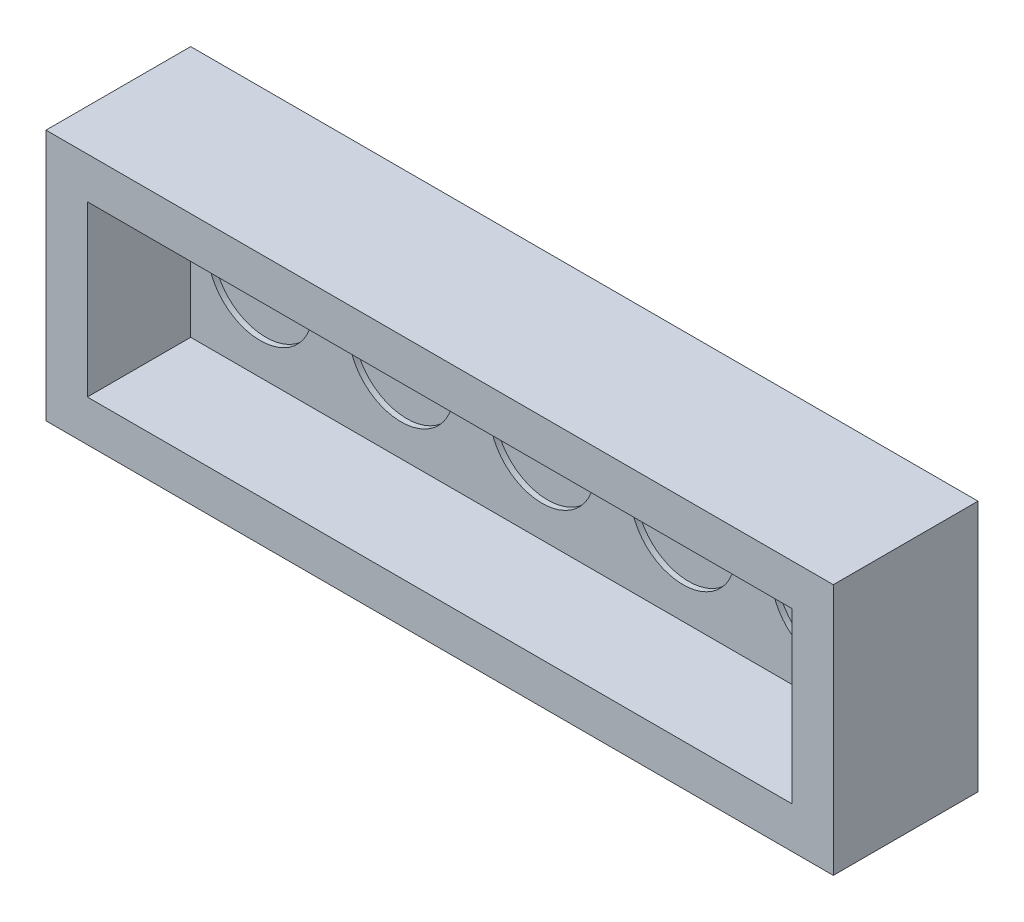
SolidWorks part; units mm, degrees
ref_plane "Front Plane" through (0, 0, 0) normal (0, 0, 1) x (1, 0, 0)
ref_plane "Top Plane" through (0, 0, 0) normal (0, 1, 0) x (1, 0, 0)
ref_plane "Right Plane" through (0, 0, 0) normal (1, 0, 0) x (0, 0, -1)
sketch "Esquisse1" plane through (0, 0, 0) normal (0, 0, 1) x (1, 0, 0)
  line L1 (0, 0) -> (419, 0)
  line L2 (0, 0) -> (0, -134)
  line L3 (0, -134) -> (419, -134)
  line L4 (419, 0) -> (419, -134)
  dimension "D1" = 419
  dimension "D2" = 134
extrude "Boss.-Extru.1" add sketch "Esquisse1" along normal blind 22
sketch "Esquisse3" plane through (0, 0, 22) normal (0, 0, 1) x (1, 0, 0)
  line L0 (0, -134) -> (0, 0)
  line L1 (0, 0) -> (0, -134) construction
  line L2 (0, 0) -> (419, 0)
  line L3 (419, -134) -> (419, 0) construction
  line L4 (419, 0) -> (419, -134)
  line L7 (397, -112) -> (397, -22)
  line L8 (397, -22) -> (22, -22)
  line L9 (22, -22) -> (22, -112)
  line L10 (419, 0) -> (0, 0) construction
  line L12 (22, -112) -> (397, -112)
  line L13 (0, -134) -> (419, -134)
  point P12 (22, -93.7254)
  dimension "D1" = 22
  dimension "D2" = 22
  dimension "D3" = 22
  dimension "D4" = 22
extrude "Boss.-Extru.2" add sketch "Esquisse3" along normal blind 55
sketch "Esquisse4" plane through (0, 0, 22) normal (0, 0, 1) x (1, 0, 0)
  line L1 (22, -112) -> (22, -22) construction
  line L2 (22, -112) -> (397, -112) construction
  circle A0 centre (59, -67) radius 28
  circle A1 centre (134, -67) radius 28
  circle A2 centre (209, -67) radius 28
  circle A3 centre (284, -67) radius 28
  circle A4 centre (359, -67) radius 28
  point P3 (60.754, -67.138)
  point P11 (0, 0)
  dimension "D1" = 56
  dimension "D3" = 45
  dimension "D4" = 37
  dimension "D2" = 5
extrude "Enlèv. mat.-Extru.1" cut sketch "Esquisse4" against normal blind 3
